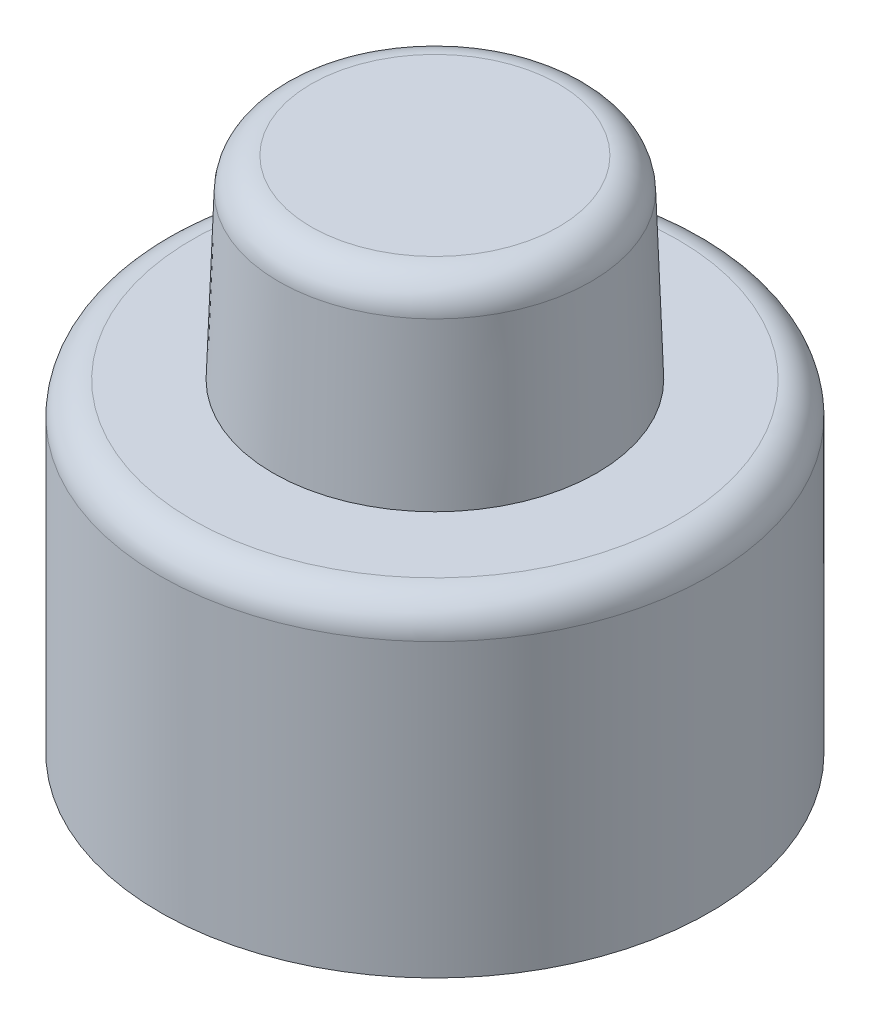
SolidWorks part; units mm, degrees
ref_plane "Front Plane" through (0, 0, 0) normal (0, 0, 1) x (1, 0, 0)
ref_plane "Top Plane" through (0, 0, 0) normal (0, 1, 0) x (1, 0, 0)
ref_plane "Right Plane" through (0, 0, 0) normal (1, 0, 0) x (0, 0, -1)
sketch "Sketch1" plane through (0, 0, 0) normal (0, 1, 0) x (1, 0, 0)
  circle A0 centre (-51.1202, 0) radius 8.5
extrude "Boss-Extrude1" add sketch "Sketch1" along normal blind 6
sketch "Sketch2" plane through (0, 6, 0) normal (0, 1, 0) x (1, 0, 0)
  circle A0 centre (-51.1202, 0) radius 5
  circle A1 centre (-51.1202, 0) radius 8.5 construction
fillet "Fillet2" radius 1 1 edges at (-51.1202, 6, 8.5)
extrude "Boss-Extrude3" add sketch "Sketch2" along normal blind 6 draft 2 contours A0
fillet "Fillet4" radius 1 1 edges at (-51.1202, 12, 4.7905)
sketch "Sketch3" plane through (0, 0, 0) normal (0, -1, 0) x (1, 0, 0)
  line L0 (-59.6202, 0) -> (-42.6202, 0) construction
  line L1 (-59.6202, 0) -> (-51.6202, 0)
  line L2 (-59.6202, 0) -> (70.3798, 0)
  line L3 (-59.6202, 0) -> (-46.6165, 0)
  line L4 (-46.6165, 0) -> (-46.6165, -7.2088)
  line L5 (-51.6202, 0) -> (-51.6202, -8.4853)
  line L7 (-51.6202, -8.4853) -> (-46.6165, -8.4853)
  line L8 (-51.6202, -8.4853) -> (-51.6202, 1.5147)
  line L9 (-51.6202, 1.5147) -> (-46.6165, 1.5147)
  line L10 (-46.6165, -8.4853) -> (-46.6165, 1.5147)
  circle A0 centre (-51.1202, 0) radius 8.5 construction
  circle M8 centre (-51.1202, 0) radius 8.5
extrude "Boss-Extrude4" add sketch "Sketch3" along normal blind 4 contours L5 L1 M8 | L10 L2 L1 L8 L9 M8 | L2 L4 M8
sketch "Sketch6" plane through (0, -4, 0) normal (0, -1, 0) x (1, 0, 0)
  line L1 (-51.6202, 1.5147) -> (-46.6165, 1.5147)
  line L2 (-51.6202, 1.5147) -> (-51.6202, -8.7002)
  line L3 (-51.6202, -8.7002) -> (-46.6165, -8.7002)
  line L4 (-46.6165, 1.5147) -> (-46.6165, -8.7002)
  arc A0 (-46.6165, -7.2088) -> (-51.6202, -8.4853) centre (-51.1202, 0) cw
  line M1 (-51.6202, -8.4853) -> (-51.6202, 1.5147)
  line M2 (-51.6202, 1.5147) -> (-46.6165, 1.5147)
  line M3 (-46.6165, 1.5147) -> (-46.6165, -7.2088)
extrude "Cut-Extrude4" cut sketch "Sketch6" against normal blind 7 contours A0 M3 M2 M1
sketch "Sketch7" plane through (0, 0, 1.5147) normal (0, 0, -1) x (-1, 0, 0)
  line L1 (51.6202, 3) -> (46.6165, 3)
  line L2 (51.6202, 3) -> (51.6202, -4)
  line L3 (51.6202, -4) -> (46.6165, -4)
  line L4 (46.6165, 3) -> (46.6165, -4)
extrude "Boss-Extrude5" add sketch "Sketch7" along normal blind 8
equation "\".5.00mm\"=1"
